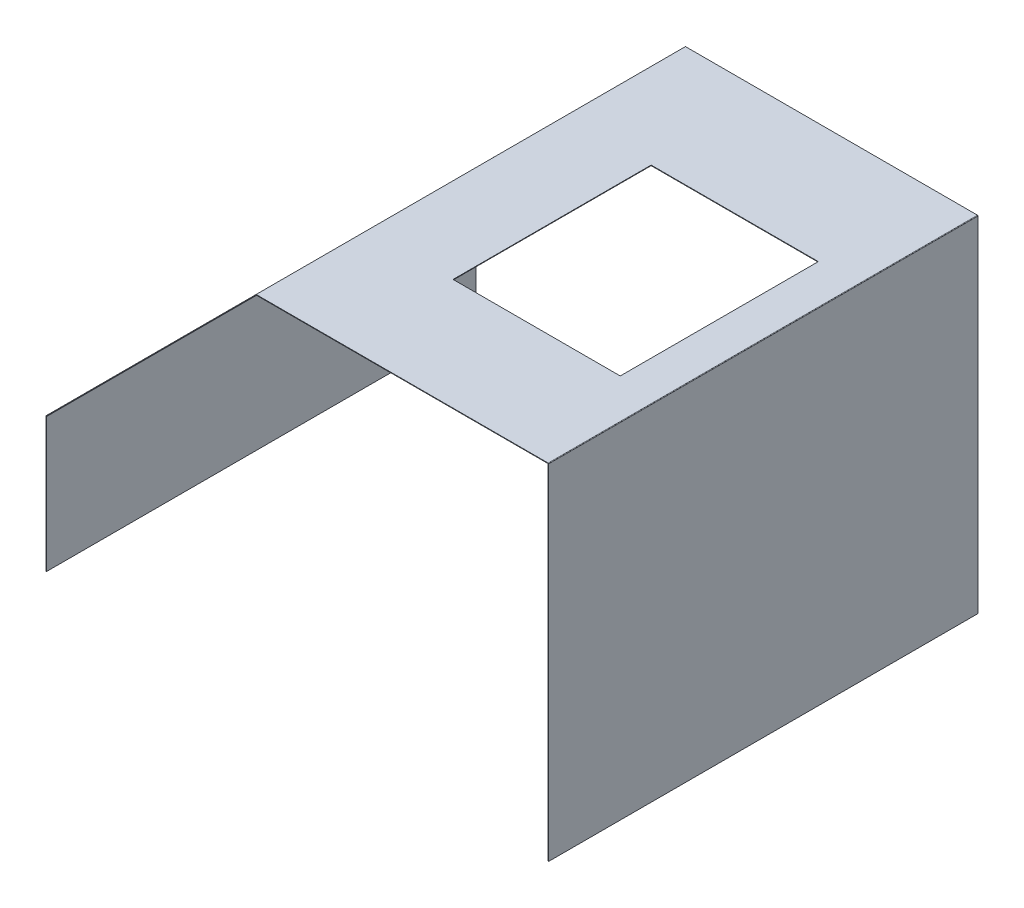
SolidWorks part; units mm, degrees
other "Carpeta de soldadura"
ref_plane "Alzado" through (0, 0, 0) normal (0, 0, 1) x (1, 0, 0)
ref_plane "Planta" through (0, 0, 0) normal (0, 1, 0) x (1, 0, 0)
ref_plane "Vista lateral" through (0, 0, 0) normal (1, 0, 0) x (0, 0, -1)
sketch "Croquis1" plane through (0, 0, 0) normal (0, 0, 1) x (1, 0, 0)
  line L0 (0, 0) -> (765, 0)
  line L1 (765, 0) -> (765, 525)
  line L2 (765, 525) -> (320, 525)
  line L3 (320, 525) -> (0, 205)
  line L4 (0, 205) -> (0, 0)
  dimension "D1" = 765
  dimension "D2" = 525
  dimension "D3" = 445
  dimension "D4" = 205
extrude "Saliente-Extruir1" add sketch "Croquis1" along normal blind 0.8357
sketch "Croquis2" plane through (0, 0, 0.8357) normal (0, 0, 1) x (1, 0, 0)
  line L15 (765.8357, 525.8357) -> (319.6539, 525.8357)
  line L16 (319.6539, 525.8357) -> (-0.8357, 205.3461)
  line L22 (-0.8357, 205.3461) -> (-0.8357, 0)
  line L24 (765.8357, 0) -> (765.8357, 525.8357)
  line L25 (0, 205) -> (0, 0)
  line L26 (0, 0) -> (765, 0)
  line L27 (765, 0) -> (765, 525)
  line L28 (765, 525) -> (320, 525)
  line L29 (320, 525) -> (0, 205)
  line L30 (0, 205) -> (0, 0)
  line L32 (765, 0) -> (765, 525)
  line L33 (765, 525) -> (320, 525)
  line L34 (320, 525) -> (0, 205)
  line L35 (0, 0) -> (-0.8357, 0)
  line L36 (-0.8357, 205.3461) -> (-0.8357, -0.8357) construction
  line L37 (-0.8357, -0.8357) -> (765.8357, -0.8357) construction
  line L38 (0, 0) -> (765, 0) construction
  line L39 (765, 0) -> (765.8357, 0)
  line L40 (765.8357, -0.8357) -> (765.8357, 525.8357) construction
  dimension "D1" = 0
  dimension "D2" = 0.8357
extrude "Saliente-Extruir2" add sketch "Croquis2" along normal blind 12.7
ref_plane "Plano1" through (0, 0, 13.5357) normal (0, 0, 1) x (1, 0, 0)
sketch "Croquis3" plane through (0, 0, 13.5357) normal (0, 0, 1) x (1, 0, 0)
  line L0 (450, 525.8357) -> (450, 525)
  line L1 (765.8357, 0) -> (765.8357, 525.8357) construction
  line L2 (765.8357, 0) -> (765.8357, 525.8357)
  line L3 (450, 525) -> (320, 525)
  line L5 (320, 525) -> (0, 205)
  line L6 (765.8357, 525.8357) -> (319.6539, 525.8357) construction
  line L7 (765, 525) -> (765, 0)
  line L8 (765, 0) -> (765.8357, 0)
  line L9 (765, 525) -> (705, 525)
  line L10 (320, 525) -> (765, 525) construction
  line L11 (705, 525) -> (705, 525.8357)
  line L12 (705, 525.8357) -> (765.8357, 525.8357)
  line L13 (0, 205) -> (0, 0)
  line L14 (0, 0) -> (-0.8357, 0)
  line L15 (-0.8357, 0) -> (-0.8357, 205.3461)
  line L16 (-0.8357, 205.3461) -> (319.6539, 525.8357)
  line L17 (319.6539, 525.8357) -> (450, 525.8357)
  dimension "D1" = 130
  dimension "D2" = 255
extrude "Saliente-Extruir3" add sketch "Croquis3" along normal blind 642.126
sketch "Croquis4" plane through (0, 0, 13.5357) normal (0, 0, 1) x (1, 0, 0)
  line L4 (705, 525.8357) -> (450, 525.8357)
  line L5 (450, 525.8357) -> (450, 525)
  line L6 (450, 525) -> (705, 525)
  line L7 (705, 525) -> (705, 525.8357)
  line L8 (705, 525.8357) -> (450, 525.8357)
  line L9 (450, 525.8357) -> (450, 525)
  line L10 (450, 525) -> (705, 525)
  line L11 (705, 525) -> (705, 525.8357)
  dimension "D1" = 0
extrude "Saliente-Extruir4" add sketch "Croquis4" along normal blind 170
sketch "Croquis5" plane through (0, 0, 655.6617) normal (0, 0, 1) x (1, 0, 0)
  line L4 (705, 525) -> (705, 525.8357)
  line L5 (705, 525.8357) -> (450, 525.8357)
  line L6 (450, 525.8357) -> (450, 525)
  line L7 (450, 525) -> (705, 525)
  line L8 (705, 525) -> (705, 525.8357)
  line L9 (705, 525.8357) -> (450, 525.8357)
  line L10 (450, 525.8357) -> (450, 525)
  line L11 (450, 525) -> (705, 525)
  dimension "D1" = 0
extrude "Saliente-Extruir5" add sketch "Croquis5" against normal blind 170
sketch "Croquis6" plane through (-103.0909, 103.0909, 0) normal (-0.7071, 0.7071, 0) x (0, 0, 1)
  line L0 (0.8357, 597.8514) -> (655.6617, 144.6107) construction
  line L1 (0.8357, 144.6107) -> (655.6617, 597.8514) construction
  line L2 (655.6617, 597.8514) -> (0.8357, 597.8514) construction
  line L3 (43.2487, 545.8514) -> (613.2487, 545.8514) construction
  line L4 (43.2487, 545.8514) -> (43.2487, 196.6107) construction
  line L5 (43.2487, 196.6107) -> (613.2487, 196.6107) construction
  line L6 (613.2487, 545.8514) -> (613.2487, 196.6107) construction
  line L7 (43.2487, 545.8514) -> (613.2487, 196.6107) construction
  line L8 (43.2487, 196.6107) -> (613.2487, 545.8514) construction
  line L9 (43.2487, 196.6107) -> (613.2487, 196.6107)
  line L10 (43.2487, 196.6107) -> (43.2487, 597.8514)
  line L11 (43.2487, 597.8514) -> (613.2487, 597.8514)
  line L12 (613.2487, 196.6107) -> (613.2487, 597.8514)
  line L13 (655.6617, 144.6107) -> (0.8357, 144.6107) construction
  point P8 (328.2487, 371.2311)
  dimension "D1" = 52
  dimension "D2" = 570
extrude "Cortar-Extruir1" cut sketch "Croquis6" against normal blind 190
sketch "Croquis7" plane through (0, 0, 0.8357) normal (0, 0, 1) x (1, 0, 0)
  line L0 (0, 0) -> (765, 0)
  line L1 (765, 0) -> (765, 525)
  line L2 (765, 525) -> (320, 525)
  line L3 (320, 525) -> (0, 205)
  line L4 (0, 205) -> (0, 0)
extrude "Cortar-Extruir2" cut sketch "Croquis7" against normal blind 174 and the other way blind 198
fillet "Redondeo3" radius 0.8 4 edges at (765.8357, 525.8357, 328.2487) (765, 525, 328.2487) (0, 205, 328.2487) (-0.8357, 205.3461, 328.2487)
